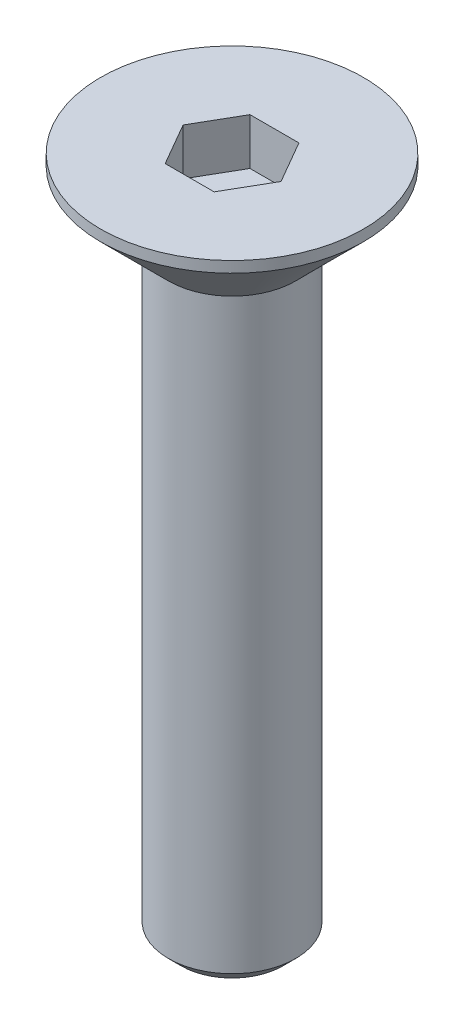
SolidWorks part; units mm, degrees
material "ACIER EZ"
ref_plane "Front Plane" through (0, 0, 0) normal (0, 0, 1) x (1, 0, 0)
ref_plane "Top Plane" through (0, 0, 0) normal (0, 1, 0) x (1, 0, 0)
ref_plane "Right Plane" through (0, 0, 0) normal (1, 0, 0) x (0, 0, -1)
sketch "Esquisse TETE" plane through (0, 0, 0) normal (0, 1, 0) x (1, 0, 0)
  line L1 (3.36, 1.9399) -> (0, 3.8798) construction
  line L2 (0, 3.8798) -> (-3.36, 1.9399) construction
  line L3 (-3.36, 1.9399) -> (-3.36, -1.9399) construction
  line L4 (-3.36, -1.9399) -> (0, -3.8798) construction
  line L5 (0, -3.8798) -> (3.36, -1.9399) construction
  line L6 (3.36, -1.9399) -> (3.36, 1.9399) construction
  circle A0 centre (0, 0) radius 3.36
  dimension "dk" = 6.72
extrude "Extrusion TETE" add sketch "Esquisse TETE" against normal blind 1.86
sketch "Esquisse1" plane through (0, 0, 0) normal (0, 1, 0) x (1, 0, 0)
  line L1 (0.5774, -1) -> (1.1547, 0)
  line L2 (1.1547, 0) -> (0.5774, 1)
  line L3 (0.5774, 1) -> (-0.5774, 1)
  line L4 (-0.5774, 1) -> (-1.1547, 0)
  line L5 (-1.1547, 0) -> (-0.5774, -1)
  line L6 (-0.5774, -1) -> (0.5774, -1)
  circle A0 centre (0, 0) radius 1 construction
  dimension "s" = 2
extrude "Enlèv. mat.-Extru.1" cut sketch "Esquisse1" against normal blind 1.1 contours L5 L6 L1 L2 L3 L4
sketch "Esquisse CORPS" plane through (0, -1.86, 0) normal (0, -1, 0) x (1, 0, 0)
  circle A0 centre (0, 0) radius 1.5
  dimension "D" = 3
extrude "Extrusion CORPS" add sketch "Esquisse CORPS" along normal blind 14.14
cosmetic thread "Représentation de filetage3" parameters "D2"=2.46
sketch "Esquisse FRAISAGE" plane through (0, 0, 0) normal (1, 0, 0) x (0, 0, -1)
  line L0 (-1.5, -1.86) -> (-3.1, -0.26)
  line L1 (-3.36, 0) -> (-3.36, -1.86) construction
  line L2 (-3.36, 0) -> (-3.36, -1.86)
  line L3 (-3.36, -1.86) -> (-1.5, -1.86)
  line L4 (0, 0) -> (0, -5.7112) construction
  line L5 (3.36, 0) -> (-3.36, 0) construction
  line L6 (-3.36, 0) -> (-3.1, 0)
  line L7 (-3.1, 0) -> (-3.1, -0.26)
  dimension "D1" = 45
  dimension "dk choisi" = 6.2
revolve "Enlèvement de matière-Révolution1" cut sketch "Esquisse FRAISAGE" angle 360 about L4
chamfer "Chanfrein" distance 0.3 1 edges at (0, -16, -1.5)
